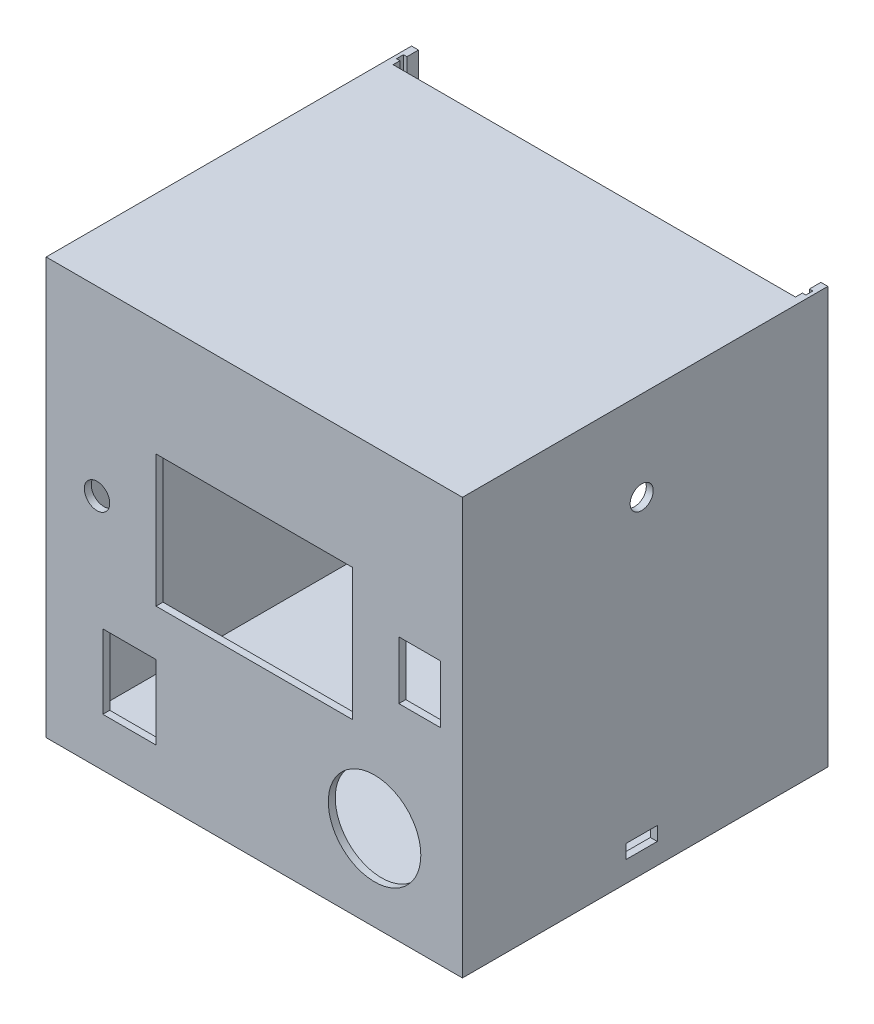
SolidWorks part; units mm, degrees
ref_plane "Front Plane" through (0, 0, 0) normal (0, 0, 1) x (1, 0, 0)
ref_plane "Top Plane" through (0, 0, 0) normal (0, 1, 0) x (1, 0, 0)
ref_plane "Right Plane" through (0, 0, 0) normal (1, 0, 0) x (0, 0, -1)
sketch "Sketch2" plane through (0, 0, 0) normal (0, 0, 1) x (1, 0, 0)
  line L0 (0, 180) -> (0, 130)
  line L1 (0, 0) -> (180, 0)
  line L2 (0, 0) -> (0, 180)
  line L3 (0, 180) -> (180, 180)
  line L4 (180, 0) -> (180, 180)
  line L5 (90, 180) -> (90, -24.0615) construction
  line L7 (47.5, 130) -> (132.5, 130)
  line L9 (47.5, 73) -> (132.5, 73)
  line L10 (132.5, 130) -> (132.5, 73)
  line L11 (47.5, 130) -> (47.5, 73)
  line L14 (152.5, 89) -> (170.5, 89)
  line L15 (152.5, 89) -> (152.5, 114)
  line L16 (152.5, 114) -> (170.5, 114)
  line L17 (170.5, 89) -> (170.5, 114)
  line L20 (47.5, 53) -> (24.5, 53)
  line L21 (47.5, 53) -> (47.5, 21)
  line L22 (47.5, 21) -> (24.5, 21)
  line L23 (24.5, 53) -> (24.5, 21)
  circle A0 centre (22, 101.5) radius 5.5
  circle A1 centre (142, 37) radius 20
  dimension "D8" = 11
  dimension "D16" = 40
  dimension "D1" = 180
  dimension "D2" = 180
  dimension "D3" = 22
  dimension "D4" = 66
  dimension "D5" = 85
  dimension "D6" = 57
  dimension "D7" = 42.5
  dimension "D9" = 18
  dimension "D10" = 25
  dimension "D11" = 20
  dimension "D12" = 142
  dimension "D13" = 50
  dimension "D14" = 78.5
  dimension "D15" = 23
  dimension "D17" = 32
  dimension "D18" = 20
  dimension "D19" = 36
  dimension "D20" = 53
extrude "Boss-Extrude1" add sketch "Sketch2" against normal blind 3 contours L5 L3 L0 L2 L1 L9 L11 L7 A0 L23 L20 L21 L22 | L3 L5 L7 L10 L9 L1 L4 L17 L14 L15 L16 A1
sketch "Sketch3" plane through (0, 0, 0) normal (1, 0, 0) x (0, 0, -1)
  line L0 (3, 90) -> (159.5262, 90) construction
  line L1 (3, 180) -> (3, 0) construction
  line L2 (50, 186.5438) -> (50, -5.0411) construction
  line L3 (3, 180) -> (3, 90)
  line L4 (50, 0) -> (158, 0)
  line L6 (3, 180) -> (158, 180)
  line L7 (158, 0) -> (158, 180)
  line L8 (3, 180) -> (3, 0)
  line L9 (3, 0) -> (50, 0)
  dimension "D1" = 155
  dimension "D2" = 47
  dimension "D3" = 180
  dimension "D4" = 90
extrude "Boss-Extrude2" add sketch "Sketch3" along normal blind 3
ref_plane "Plane1" through (90, 0, 0) normal (1, 0, 0) x (0, 0, -1)
mirror "Mirror1" about plane through (90, 0, 0) normal (1, 0, 0) of "Boss-Extrude2"
sketch "Sketch4" plane through (0, 0, 0) normal (0, 1, 0) x (1, 0, 0)
  line L0 (180, 79) -> (-25.8206, 79) construction
  line L1 (180, 0) -> (0, 0)
  line L2 (180, 0) -> (180, 158)
  line L3 (180, 158) -> (0, 158)
  line L4 (0, 0) -> (0, 158)
  dimension "D1" = 158
  dimension "D2" = 180
extrude "Boss-Extrude3" add sketch "Sketch4" along normal blind 3 contours L2 L3 L4 L1
sketch "Sketch5" plane through (0, 0, 0) normal (1, 0, 0) x (0, 0, -1)
  line L0 (158, 180) -> (0, 180) construction
  line L1 (158, 0) -> (158, 180) construction
  line L5 (70, 11) -> (85, 11)
  line L6 (70, 11) -> (70, 20.5)
  line L7 (70.5, 21) -> (84.5, 21)
  line L8 (85, 11) -> (85, 20.5)
  circle A0 centre (83.5, 141.3) radius 5
  arc A1 (70, 20.5) -> (70.5, 21) centre (70.5, 20.5) cw
  arc A2 (85, 20.5) -> (84.5, 21) centre (84.5, 20.5) ccw
  point P3 (6, 180)
  point P6 (3, 180)
  point P8 (77.5, 21)
  point P18 (70, 21)
  point P21 (85, 21)
  dimension "D1" = 10
  dimension "D11" = 0.5
  dimension "D2" = 38.7
  dimension "D3" = 155
  dimension "D4" = 3
  dimension "D5" = 77.5
  dimension "D6" = 11
  dimension "D7" = 15
  dimension "D8" = 7.5
  dimension "D9" = 10
  dimension "D10" = 77.5
ref_plane "Plane2" through (0, 180, 0) normal (0, 1, 0) x (1, 0, 0)
sketch "Sketch6" plane through (0, 180, 0) normal (0, 1, 0) x (1, 0, 0)
  line L0 (-5.7298, 48.5) -> (184.077, 48.5) construction
  line L1 (90, -3.8803) -> (90, 144.6043) construction
  line L2 (90, -69.143) -> (90, 69.143) construction
  line L3 (0, 158) -> (0, 0) construction
  line L4 (3, 153) -> (1.5, 153)
  line L5 (3, 3) -> (3, 158) construction
  line L6 (1.5, 153) -> (1.5, 150)
  line L7 (1.5, 150) -> (3, 150)
  line L8 (3, 3) -> (3, 158) construction
  line L9 (3, 158) -> (0, 158) construction
  line L10 (3, 150) -> (3, 153)
  dimension "D1" = 5
  dimension "D2" = 3
  dimension "D3" = 1.5
extrude "Cut-Extrude4" cut sketch "Sketch6" against normal up to surface (177 mm away) contours L6 L7 L10 L4 up to face at (90, 3, -80.5)
mirror "Mirror2" about plane through (90, 0, 0) normal (1, 0, 0) of "Cut-Extrude4"
sketch "Sketch8" plane through (0, 180, 0) normal (0, 1, 0) x (1, 0, 0)
  line L0 (180, 158) -> (180, 0) construction
  line L1 (0, 0) -> (180, 0)
  line L2 (0, 0) -> (0, 147)
  line L3 (0, 147) -> (180, 147)
  line L4 (180, 0) -> (180, 147)
  dimension "D1" = 147
extrude "Boss-Extrude5" add sketch "Sketch8" against normal blind 3
ref_plane "Plane3" through (180, 0, 0) normal (1, 0, 0) x (0, 0, -1)
sketch "Sketch9" plane through (180, 0, 0) normal (1, 0, 0) x (0, 0, -1)
  line L0 (158, 180) -> (0, 180) construction
  line L1 (158, 0) -> (0, 0) construction
  line L2 (70.75, 9) -> (84.25, 9)
  line L3 (70.75, 9) -> (70.75, 15)
  line L4 (70.75, 15) -> (84.25, 15)
  line L5 (84.25, 9) -> (84.25, 15)
  line L6 (70.75, 9) -> (84.25, 15) construction
  line L7 (70.75, 15) -> (84.25, 9) construction
  circle A1 centre (77.5, 141.3) radius 5
  point P1 (0, 180)
  point P2 (77.5, 12)
  point P7 (155, 180)
  point P11 (0, 0)
  point P12 (155, 0)
  dimension "D1" = 10
  dimension "D2" = 38.7
  dimension "D3" = 155
  dimension "D4" = 77.5
  dimension "D5" = 13.5
  dimension "D6" = 6
  dimension "D7" = 155
  dimension "D8" = 77.5
  dimension "D9" = 9
extrude "Cut-Extrude5" cut sketch "Sketch9" against normal blind 10
